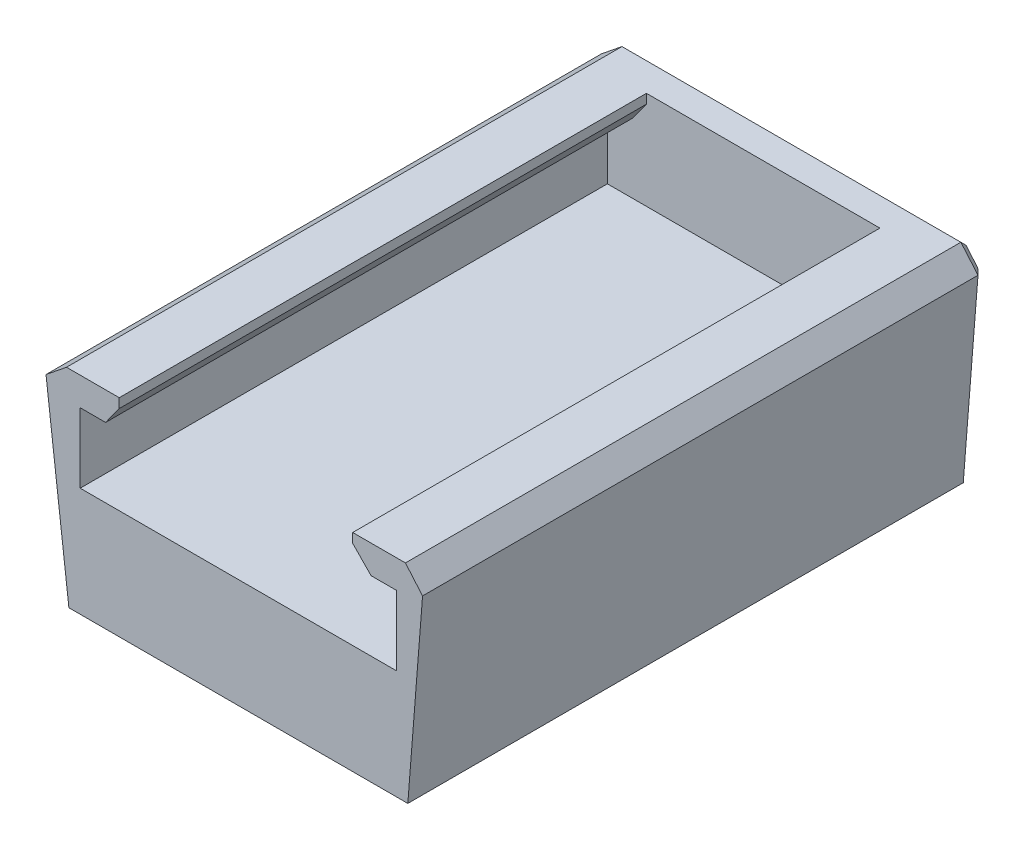
SolidWorks part; units mm, degrees
ref_plane "Front Plane" through (0, 0, 0) normal (0, 0, 1) x (1, 0, 0)
ref_plane "Top Plane" through (0, 0, 0) normal (0, 1, 0) x (1, 0, 0)
ref_plane "Right Plane" through (0, 0, 0) normal (1, 0, 0) x (0, 0, -1)
sketch "Sketch1" plane through (0, 0, 0) normal (0, 0, 1) x (1, 0, 0)
  line L0 (-17.076, -1.6995) -> (0.924, -1.6995)
  line L3 (0.324, 7.8005) -> (0.324, 4.1005)
  line L4 (-16.476, 4.1005) -> (-16.476, 7.8005)
  line L5 (-17.2028, 9.3005) -> (-18.2922, 8.4212)
  line L6 (-18.2922, 8.4212) -> (-17.076, -1.6995)
  line L7 (0.7972, 9.3005) -> (1.7069, 8.2364)
  line L8 (1.7069, 8.2364) -> (0.924, -1.6995)
  line L10 (0.324, 4.1005) -> (-16.476, 4.1005)
  line L11 (0.324, 7.8005) -> (-1.026, 7.8005)
  line L12 (-16.476, 7.8005) -> (-15.126, 7.8005)
  line L13 (0.7972, 9.3005) -> (-2.0028, 9.3005)
  line L14 (-17.2028, 9.3005) -> (-14.4028, 9.3005)
  line L17 (-14.4028, 9.3005) -> (-14.4028, 8.8005)
  line L18 (-2.0028, 9.3005) -> (-2.0028, 8.8005)
  line L19 (-14.4028, 8.8005) -> (-15.126, 7.8005)
  line L21 (-1.026, 7.8005) -> (-2.0028, 8.8005)
  dimension "D2" = 3.7
  dimension "D3" = 2.8
  dimension "D4" = 2.8
  dimension "D5" = 18
  dimension "D6" = 18
  dimension "D7" = 20
  dimension "D8" = 1.4
  dimension "D9" = 1.4
  dimension "D10" = 0.5
  dimension "D11" = 0.5
extrude "Boss-Extrude1" add sketch "Sketch1" against normal blind 30
ref_plane "Plane1" through (0, 0, -30) normal (0, 0, -1) x (-1, 0, 0)
sketch "Sketch2" plane through (0, 0, -30) normal (0, 0, -1) x (-1, 0, 0)
  line L0 (2.0028, 9.3005) -> (14.4028, 9.3005)
  line L1 (-0.324, 4.1005) -> (-0.324, 9.3005)
  line L2 (-0.7972, 9.3005) -> (2.0028, 9.3005) construction
  line L3 (-0.324, 9.3005) -> (2.0028, 9.3005)
  line L4 (-0.324, 4.1005) -> (16.476, 4.1005)
  line L5 (16.476, 4.1005) -> (16.476, 9.3005)
  line L6 (14.4028, 9.3005) -> (17.2028, 9.3005) construction
  line L7 (16.476, 9.3005) -> (14.4028, 9.3005)
extrude "Boss-Extrude2" add sketch "Sketch2" against normal blind 2
chamfer "Chamfer8" distance 0.5 angle 45 6 edges at (-17.6841, 3.3609, -30) (-8.076, -1.6995, -30) (1.3155, 3.2685, -30) (1.2521, 8.7685, -30) (-8.2028, 9.3005, -30) (-17.7475, 8.8609, -30)
